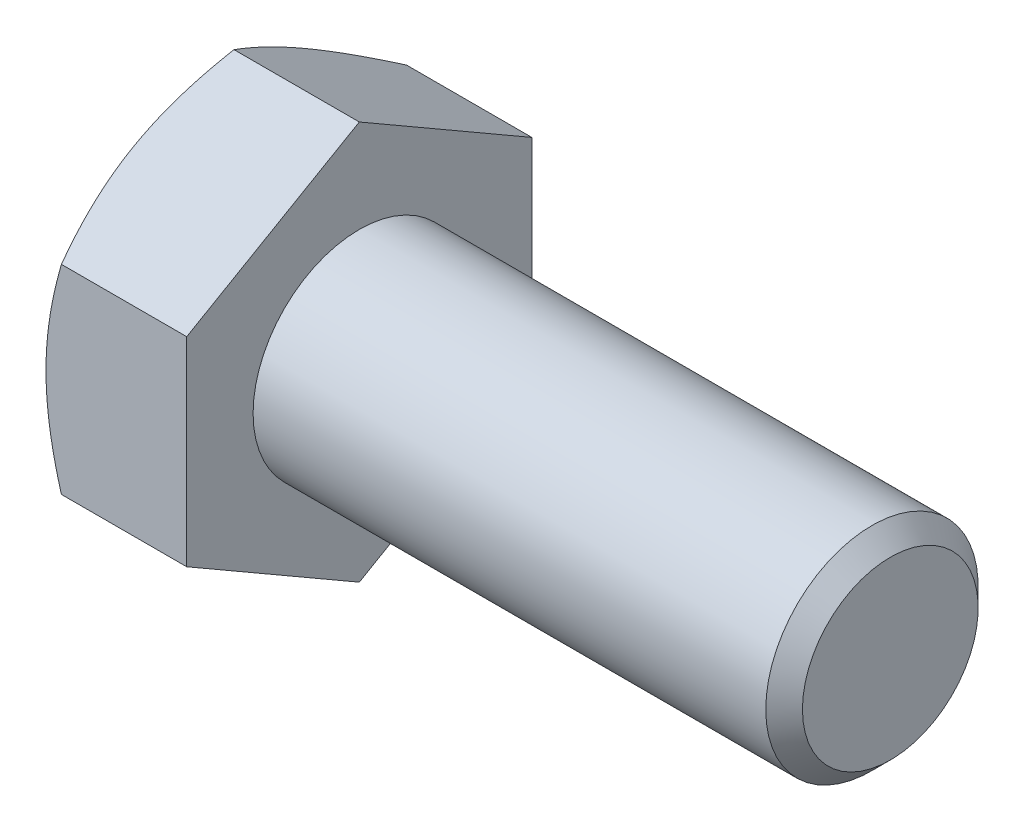
SolidWorks part; units mm, degrees
extrude "BaseHead" add sketch "Sketch1" along normal blind 5.3
sketch "Sketch1" plane through (0, 0, 0) normal (1, 0, 0) x (0, 0, -1)
  line L0 (6.5, 3.7528) -> (6.5, -3.7528)
  line L1 (-6.5, 3.7528) -> (-6.5, -3.7528)
  line L2 (6.5, -3.7528) -> (0, -7.5056)
  line L3 (0, -7.5056) -> (-6.5, -3.7528)
  line L4 (6.5, 3.7528) -> (0, 7.5056)
  line L5 (0, 7.5056) -> (-6.5, 3.7528)
  dimension "Width_flats" = 13
  dimension "D2" = 120
  dimension "D3" = 6.5
  dimension "D4" = 6.5
  dimension "D5" = 6.5
ref_plane "Plane1" through (0, 0, 0) normal (0, 0, 1) x (1, 0, 0)
ref_plane "Plane2" through (0, 0, 0) normal (0, 1, 0) x (1, 0, 0)
ref_plane "Plane3" through (0, 0, 0) normal (1, 0, 0) x (0, 0, -1)
sketch "BodySke" plane through (0, 0, 0) normal (0, 0, 1) x (1, 0, 0)
  line L1 (0, 0) -> (25.3, 0)
  line L2 (0, 0) -> (0, 4)
  line L4 (25.3, 0) -> (25.3, 3.3095)
  line L5 (5.3, 7.5056) -> (5.3, 3.7528) construction
  line L6 (25.3, 3.3095) -> (24.6095, 4)
  line L7 (0, 0) -> (110.49, 0) construction
  line L8 (25.3, -3.3095) -> (24.6095, -4) construction
  line L9 (0, 3.7528) -> (0, -3.7528) construction
  line L10 (6.55, 15.24) -> (6.55, -1.27) construction
  line L11 (3.3, 15.24) -> (3.3, -1.27) construction
  line L12 (5.3, 3.7528) -> (5.3, -3.7528) construction
  line L15 (0, 4) -> (24.6095, 4)
  dimension "Body_ch_ang" = 45
  dimension "Minor_dia" = 6.619
  dimension "Diameter" = 8
  dimension "Advance" = 1.25
revolve "BaseBody" add sketch "BodySke" angle 360 about L7
cosmetic thread "ThreadCosmetic" [suppressed] parameters "Thread_length"=18.75, "Thread_minor"=6.619
fillet "HeadFillet" [suppressed] radius 0.4
sketch "Sketch3" plane through (0, 0, 0) normal (0, 0, 1) x (1, 0, 0)
  line L0 (0, 6.5) -> (3.4673, 12.5056)
  line L1 (0, 7.5056) -> (0, 3.7528) construction
  line L2 (3.4673, 12.5056) -> (3.4673, 17.5056)
  line L3 (3.4673, 17.5056) -> (-10, 17.5056)
  line L4 (-10, 17.5056) -> (-10, 6.5)
  line L5 (-10, 6.5) -> (0, 6.5)
  line L6 (0, 0) -> (99.06, 0) construction
  line L7 (5.3, 7.5056) -> (0, 7.5056) construction
  dimension "D1" = 6.5
  dimension "D2" = 5
  dimension "D3" = 10
  dimension "D4" = 5
  dimension "Head_ch_ang" = 30
revolve "HeadChamfer" cut sketch "Sketch3" angle 360 about L6
sketch "ThdSchSke" plane through (0, 0, 0) normal (0, 0, 1) x (1, 0, 0)
  line L0 (6.55, -3.3095) -> (6.0665, -4)
  line L1 (6.55, -3.3095) -> (7.0335, -4)
  line L2 (7.0335, -4) -> (7.0335, -5)
  line L3 (-3.175, 0) -> (5.1513, 0) construction
  line L5 (7.0335, -5) -> (6.0665, -5)
  line L6 (6.0665, -5) -> (6.0665, -4)
  dimension "Thread_minor" = 6.619
  dimension "Diameter" = 8
  dimension "Start" = 6.55
revolve "ThreadSchematic" [suppressed] cut sketch "ThdSchSke" angle 360 about L3
pattern_linear "ThdSchPat" [suppressed]
equation "\"D3@Sketch1\" = \"Width_flats@Sketch1\" / 2"
equation "\"D4@Sketch1\" = \"D3@Sketch1\""
equation "\"D5@Sketch1\" = \"D4@Sketch1\""
equation "\"Thread_minor@ThreadCosmetic\" = \"Minor_dia@BodySke\""
equation "\"D1@Sketch3\" = \"Width_flats@Sketch1\" / 2"
equation "\"Thread_length@ThreadCosmetic\" = ((sgn( (\"Length@BodySke\" - \"Advance@BodySke\" ) - \"Thread_nom@BodySke\" )-1)*( (\"Length@BodySke\" - \"Advance@BodySke\" ) - \"Thread_nom@BodySke\" ))/-2+ \"Thread_nom@BodySke\""
equation "\"Thread_minor@ThdSchSke\" = \"Minor_dia@BodySke\""
equation "\"Diameter@ThdSchSke\" = \"Diameter@BodySke\""
equation "\"Overcut@ThdSchSke\" = \"Diameter@BodySke\" * 1.25"
equation "\"Start@ThdSchSke\" = \"Head_ht@BaseHead\" + \"Length@BodySke\" - \"Thread_length@ThreadCosmetic\"  '---Non-countersunk---"
equation "\"Num_threads@ThdSchPat\" = int( \"Thread_length@ThreadCosmetic\" / \"Advance@BodySke\" + 0.999 )  + 1"
equation "\"Advance@ThdSchPat\" = \"Thread_length@ThreadCosmetic\" /  (\"Num_threads@ThdSchPat\" - 1) 'relax it"
equation "\"Num_threads@ThdSchPat\" = \"Num_threads@ThdSchPat\" - sgn( \"Num_threads@ThdSchPat\" - 1) '---chamfered tips only---"
